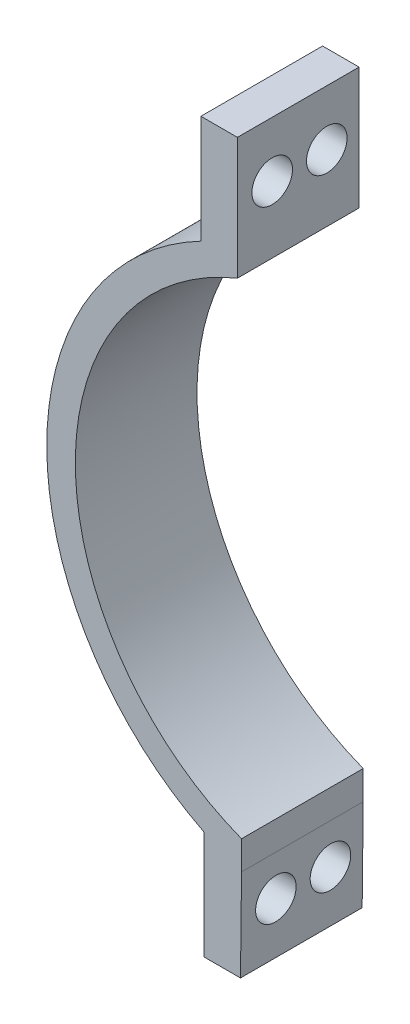
SolidWorks part; units mm, degrees
ref_plane "Front Plane" through (0, 0, 0) normal (1, 0, 0) x (0, 1, 0)
ref_plane "Top Plane" through (0, 0, 0) normal (0, 0, 1) x (0, 1, 0)
ref_plane "Right Plane" through (0, 0, 0) normal (0, 1, 0) x (-1, 0, 0)
sketch "Sketch3" plane through (0, 0, 0) normal (0, 0, 1) x (0, 1, 0)
  line L0 (-104.4458, -1.5294) -> (-93.8134, -1.5294)
  line L1 (84.9409, 0) -> (95.9609, 0)
  arc A0 (-104.4458, -1.5294) -> (95.9609, 0) centre (-3.9767, -35.5888) cw
  arc A1 (-93.8134, -1.5294) -> (84.9409, 0) centre (-4.1329, -36.2162) cw
extrude "Boss-Extrude1" add sketch "Sketch3" along normal blind 45
ref_plane "Plane1" through (0, 95.9609, 45) normal (0, 0, -1) x (-1, 0, 0)
sketch "Sketch7" plane through (0, 95.9609, 45) normal (0, 0, -1) x (1, 0, 0)
  line L0 (-13.5, 5.8931) -> (-13.5, -34.1069)
  line L1 (-13.5, -34.1069) -> (0, -34.1069)
  line L2 (0, -34.1069) -> (0, 0)
  line L3 (0, 0) -> (-13.5, 5.8931)
  arc A0 (1.5294, 200.4067) -> (0, 0) centre (35.5888, 99.9376) ccw construction
  dimension "D1" = 40
  dimension "D2" = 13.5
extrude "Boss-Extrude4" add sketch "Sketch7" along normal blind 45
ref_plane "Plane2" through (1.5294, -104.4458, 0) normal (0, 0, -1) x (-1, 0, 0)
sketch "Sketch8" plane through (1.5294, -104.4458, 0) normal (0, 0, -1) x (1, 0, 0)
  line L0 (-13.8912, -5.8392) -> (-13.8912, 34.1608)
  line L1 (-13.8912, 34.1608) -> (-0.3912, 34.1608)
  line L2 (-0.3912, 34.1608) -> (0, 0)
  line L3 (0, 0) -> (-13.8912, -5.8392)
  arc A0 (0, 0) -> (-15.0294, -194.5137) centre (34.0594, -100.4691) ccw construction
  dimension "D1" = 40
  dimension "D2" = 13.5
extrude "Boss-Extrude5" add sketch "Sketch8" against normal blind 45
sketch "Sketch9" plane through (-12.3618, 0, 0) normal (-1, 0, 0) x (0, -1, 0)
  circle A0 centre (119.4818, 11.9444) radius 7.5
  circle A1 centre (119.4818, 32.1335) radius 7.5
  circle A2 centre (-109.597, 11.9444) radius 7.5
  circle A3 centre (-109.597, 32.1335) radius 7.5
  dimension "D1" = 15
extrude "Cut-Extrude1" cut sketch "Sketch9" against normal mid plane 85
